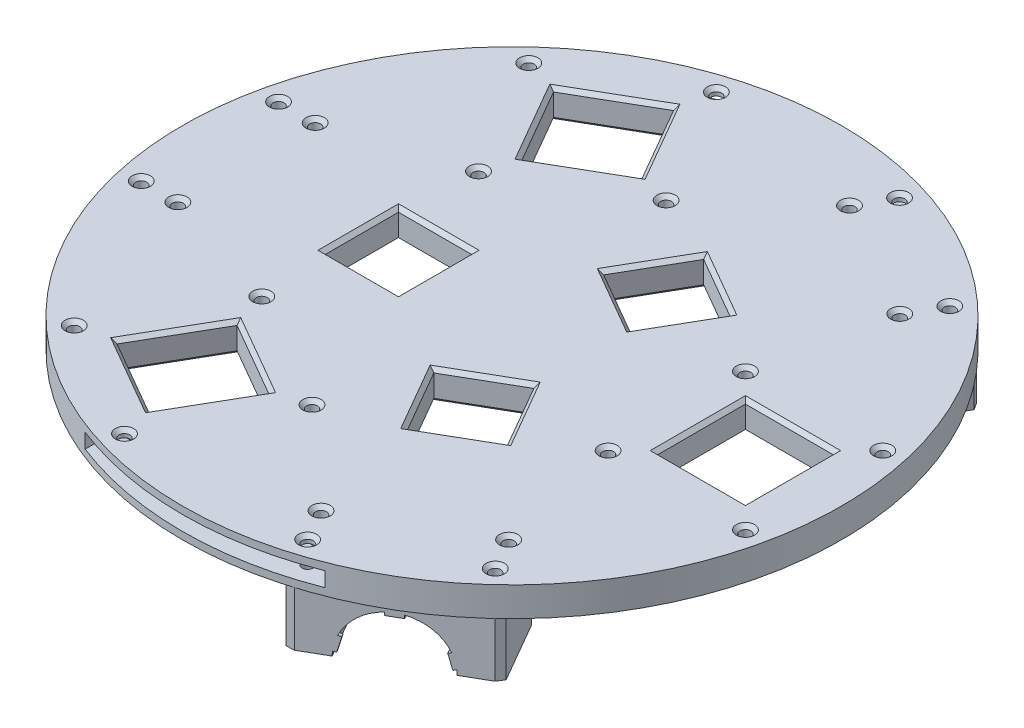
SolidWorks part; units mm, degrees
ref_plane "Plano frontal" through (0, 0, 0) normal (0, 0, 1) x (1, 0, 0)
ref_plane "Plano superior" through (0, 0, 0) normal (0, 1, 0) x (1, 0, 0)
ref_plane "Plano direito" through (0, 0, 0) normal (1, 0, 0) x (0, 0, -1)
sketch "Esboço2" plane through (0, 0, 0) normal (0, 1, 0) x (1, 0, 0)
  circle A0 centre (0, 0) radius 90
extrude "Ressalto-extrusão1" add sketch "Esboço2" along normal blind 8 contours A0
sketch "Esboço3" plane through (0, 0, 0) normal (0, -1, 0) x (-1, 0, 0)
  line L1 (67.5, 0) -> (67.5, -22)
  line L2 (67.5, 0) -> (67.5, 22)
  line L3 (67.5, -22) -> (86.5, -22)
  line L4 (87.5, -20) -> (87.5, 20)
  line L5 (86.5, 22) -> (67.5, 22)
  line L12 (87.5, -20) -> (86.5, -22)
  line L13 (87.5, 20) -> (86.5, 22)
  line L15 (-33.75, 58.4567) -> (-14.6974, 69.4567)
  line L16 (-33.75, 58.4567) -> (-52.8026, 47.4567)
  line L17 (-14.6974, 69.4567) -> (-24.1974, 85.9112)
  line L18 (-26.4295, 85.7772) -> (-61.0705, 65.7772)
  line L19 (-62.3026, 63.9112) -> (-52.8026, 47.4567)
  line L20 (-26.4295, 85.7772) -> (-24.1974, 85.9112)
  line L21 (-61.0705, 65.7772) -> (-62.3026, 63.9112)
  line L23 (-33.75, -58.4567) -> (-52.8026, -47.4567)
  line L24 (-33.75, -58.4567) -> (-14.6974, -69.4567)
  line L25 (-52.8026, -47.4567) -> (-62.3026, -63.9112)
  line L26 (-61.0705, -65.7772) -> (-26.4295, -85.7772)
  line L27 (-24.1974, -85.9112) -> (-14.6974, -69.4567)
  line L28 (-61.0705, -65.7772) -> (-62.3026, -63.9112)
  line L29 (-26.4295, -85.7772) -> (-24.1974, -85.9112)
extrude "Ressalto-extrusão2" add sketch "Esboço3" along normal blind 15
ref_plane "Plano2" through (0, 0, -90) normal (0, 0, -1) x (-1, 0, 0)
sketch "Esboço8" plane through (0, 0, -90) normal (0, 0, -1) x (-1, 0, 0)
  line L1 (0, 2) -> (32.75, 2)
  line L2 (32.75, 2) -> (32.75, 6)
  line L3 (32.75, 6) -> (-32.75, 6)
  line L4 (-32.75, 6) -> (-32.75, 2)
  line L5 (-32.75, 2) -> (0, 2)
extrude "Corte-extrusão1" cut sketch "Esboço8" against normal blind 14.5 contours L1 L2 L3 L4 L5
ref_plane "Plano3" through (0, 0, 90) normal (0, 0, 1) x (1, 0, 0)
sketch "Esboço9" plane through (0, 0, 90) normal (0, 0, 1) x (1, 0, 0)
  line L1 (0, 2) -> (32.75, 2)
  line L2 (32.75, 2) -> (32.75, 6)
  line L3 (32.75, 6) -> (-32.75, 6)
  line L4 (-32.75, 6) -> (-32.75, 2)
  line L5 (-32.75, 2) -> (0, 2)
extrude "Corte-extrusão2" cut sketch "Esboço9" against normal blind 14.5 contours L1 L2 L3 L4 L5
sketch "Esboço14" plane through (-67.5, 0, 0) normal (1, 0, 0) x (0, 0, -1)
  line L0 (22, -15) -> (-22, -15) construction
  line L3 (0, -3.5) -> (-2, -3.5)
  line L4 (0, -3.5) -> (2, -3.5)
  line L5 (2, -3.5) -> (2, -2.661)
  line L6 (-2, -3.5) -> (-2, -2.661)
  line L9 (-11.1081, -12.0236) -> (-11.6258, -13.9554)
  line L10 (-11.1081, -12.0236) -> (-10.5905, -10.0917)
  line L11 (-10.5905, -10.0917) -> (-11.4009, -9.8746)
  line L12 (-11.6258, -13.9554) -> (-12.4362, -13.7383)
  line L15 (11.1081, -12.0236) -> (10.5905, -10.0917)
  line L16 (11.1081, -12.0236) -> (11.6258, -13.9554)
  line L17 (11.6258, -13.9554) -> (12.4362, -13.7383)
  line L18 (10.5905, -10.0917) -> (11.4009, -9.8746)
  arc A0 (-12.4362, -13.7383) -> (12.4362, -13.7383) centre (0, -15) ccw
  arc A1 (-2, -2.661) -> (-11.4009, -9.8746) centre (0, -15) ccw
  arc A2 (11.4009, -9.8746) -> (2, -2.661) centre (0, -15) ccw
extrude "Corte-extrusão3" cut sketch "Esboço14" against normal through all
sketch "Esboço15" plane through (33.75, 0, 58.4567) normal (-0.5, 0, -0.866) x (-0.866, 0, 0.5)
  line L0 (22, -15) -> (-22, -15) construction
  line L3 (0, -3.5) -> (2, -3.5)
  line L4 (0, -3.5) -> (-2, -3.5)
  line L5 (-2, -3.5) -> (-2, -2.661)
  line L6 (2, -3.5) -> (2, -2.661)
  line L9 (-11.1081, -12.0236) -> (-10.5905, -10.0917)
  line L10 (-11.1081, -12.0236) -> (-11.6258, -13.9554)
  line L11 (-11.6258, -13.9554) -> (-12.4362, -13.7383)
  line L12 (-10.5905, -10.0917) -> (-11.4009, -9.8746)
  line L15 (11.1081, -12.0236) -> (11.6258, -13.9554)
  line L16 (11.1081, -12.0236) -> (10.5905, -10.0917)
  line L17 (10.5905, -10.0917) -> (11.4009, -9.8746)
  line L18 (11.6258, -13.9554) -> (12.4362, -13.7383)
  arc A0 (11.4009, -9.8746) -> (2, -2.661) centre (0, -15) ccw
  arc A1 (-2, -2.661) -> (-11.4009, -9.8746) centre (0, -15) ccw
  arc A2 (-12.4362, -13.7383) -> (12.4362, -13.7383) centre (0, -15) ccw
extrude "Corte-extrusão4" cut sketch "Esboço15" against normal through all
sketch "Esboço16" plane through (33.75, 0, -58.4567) normal (-0.5, 0, 0.866) x (0.866, 0, 0.5)
  line L0 (22, -15) -> (-22, -15) construction
  line L3 (0, -3.5) -> (2, -3.5)
  line L4 (0, -3.5) -> (-2, -3.5)
  line L5 (-2, -3.5) -> (-2, -2.661)
  line L6 (2, -3.5) -> (2, -2.661)
  line L9 (-11.1081, -12.0236) -> (-10.5905, -10.0917)
  line L10 (-11.1081, -12.0236) -> (-11.6258, -13.9554)
  line L11 (-11.6258, -13.9554) -> (-12.4362, -13.7383)
  line L12 (-10.5905, -10.0917) -> (-11.4009, -9.8746)
  line L15 (11.1081, -12.0236) -> (11.6258, -13.9554)
  line L16 (11.1081, -12.0236) -> (10.5905, -10.0917)
  line L17 (10.5905, -10.0917) -> (11.4009, -9.8746)
  line L18 (11.6258, -13.9554) -> (12.4362, -13.7383)
  arc A0 (11.4009, -9.8746) -> (2, -2.661) centre (0, -15) ccw
  arc A1 (-2, -2.661) -> (-11.4009, -9.8746) centre (0, -15) ccw
  arc A2 (-12.4362, -13.7383) -> (12.4362, -13.7383) centre (0, -15) ccw
extrude "Corte-extrusão5" cut sketch "Esboço16" against normal through all
sketch "Esboço17" plane through (33.75, 0, 58.4567) normal (-0.5, 0, -0.866) x (-0.866, 0, 0.5)
  circle A0 centre (0, -15) radius 12.5
extrude "Corte-extrusão6" cut sketch "Esboço17" against normal blind 19
sketch "Esboço18" plane through (-67.5, 0, 0) normal (1, 0, 0) x (0, 0, -1)
  circle A0 centre (0, -15) radius 12.5
extrude "Corte-extrusão7" cut sketch "Esboço18" against normal blind 19 contours A0
sketch "Esboço19" plane through (33.75, 0, -58.4567) normal (-0.5, 0, 0.866) x (0.866, 0, 0.5)
  circle A0 centre (0, -15) radius 12.5
extrude "Corte-extrusão8" cut sketch "Esboço19" against normal blind 19
sketch "Esboço20" plane through (0, -15, 0) normal (0, -1, 0) x (1, 0, 0)
  circle A0 centre (-82.5, 18.75) radius 1.5
  circle A1 centre (-72.5, 18.75) radius 1.5
  circle A2 centre (-82.5, -18.75) radius 1.5
  circle A3 centre (-72.5, -18.75) radius 1.5
  circle A4 centre (25.012, -80.8221) radius 1.5
  circle A5 centre (20.012, -72.1618) radius 1.5
  circle A6 centre (57.488, -62.0721) radius 1.5
  circle A7 centre (52.488, -53.4118) radius 1.5
  circle A8 centre (57.488, 62.0721) radius 1.5
  circle A9 centre (52.488, 53.4118) radius 1.5
  circle A10 centre (25.012, 80.8221) radius 1.5
  circle A11 centre (20.012, 72.1618) radius 1.5
extrude "Corte-extrusão9" cut sketch "Esboço20" against normal through all
sketch "Esboço21" plane through (0, 0, 0) normal (0, -1, 0) x (-1, 0, 0)
  line L0 (-10.5, 18.1865) -> (-1.8397, 23.1865)
  line L1 (21, 0) -> (21, -10)
  line L2 (21, -10) -> (41, -10)
  line L3 (41, -10) -> (41, 10)
  line L4 (41, 10) -> (21, 10)
  line L5 (21, 10) -> (21, 0)
  line L6 (-1.8397, 23.1865) -> (-11.8397, 40.507)
  line L7 (-51.75, 0) -> (-51.75, -12)
  line L8 (-51.75, -12) -> (-75.75, -12)
  line L9 (-75.75, -12) -> (-75.75, 12)
  line L10 (-75.75, 12) -> (-51.75, 12)
  line L11 (-51.75, 12) -> (-51.75, 0)
  line L13 (-11.8397, 40.507) -> (-29.1603, 30.507)
  line L14 (-29.1603, 30.507) -> (-19.1603, 13.1865)
  line L15 (-19.1603, 13.1865) -> (-10.5, 18.1865)
  line L16 (25.875, -44.8168) -> (36.2673, -38.8168)
  line L17 (36.2673, -38.8168) -> (48.2673, -59.6014)
  line L18 (48.2673, -59.6014) -> (27.4827, -71.6014)
  line L19 (27.4827, -71.6014) -> (15.4827, -50.8168)
  line L20 (15.4827, -50.8168) -> (25.875, -44.8168)
  line L22 (-10.5, -18.1865) -> (-19.1603, -13.1865)
  line L23 (-19.1603, -13.1865) -> (-29.1603, -30.507)
  line L24 (-29.1603, -30.507) -> (-11.8397, -40.507)
  line L25 (-11.8397, -40.507) -> (-1.8397, -23.1865)
  line L26 (-1.8397, -23.1865) -> (-10.5, -18.1865)
  line L27 (25.875, 44.8168) -> (15.4827, 50.8168)
  line L28 (15.4827, 50.8168) -> (27.4827, 71.6014)
  line L29 (27.4827, 71.6014) -> (48.2673, 59.6014)
  line L30 (48.2673, 59.6014) -> (36.2673, 38.8168)
  line L31 (36.2673, 38.8168) -> (25.875, 44.8168)
  circle A0 centre (-45, -18.75) radius 1.5
  circle A1 centre (-82.5, -18.75) radius 1.5
  circle A2 centre (-82.5, 18.75) radius 1.5
  circle A3 centre (-45, 18.75) radius 1.5
  circle A4 centre (38.738, -29.5961) radius 1.5
  circle A5 centre (57.488, -62.0721) radius 1.5
  circle A6 centre (25.012, -80.8221) radius 1.5
  circle A7 centre (6.262, -48.3461) radius 1.5
  circle A8 centre (6.262, 48.3461) radius 1.5
  circle A9 centre (25.012, 80.8221) radius 1.5
  circle A10 centre (57.488, 62.0721) radius 1.5
  circle A11 centre (38.738, 29.5961) radius 1.5
extrude "Corte-extrusão10" cut sketch "Esboço21" against normal through all
chamfer "Chanfro5" distance 1 angle 45 24 edges at (20.012, 8, -73.6618) (25.012, 8, -82.3221) (57.488, 8, -63.5721) (52.488, 8, -54.9118) (82.5, 8, -20.25) (82.5, 8, 17.25) (45, 8, -20.25) (45, 8, 17.25) (-25.012, 8, -82.3221) (-6.262, 8, -49.8461) (57.488, 8, 60.5721) (52.488, 8, 51.9118) (25.012, 8, 79.3221) (20.012, 8, 70.6618) (-38.738, 8, -31.0961) (-57.488, 8, -63.5721) (-72.5, 8, -20.25) (-82.5, 8, -20.25) (-82.5, 8, 17.25) (-72.5, 8, 17.25) (-6.262, 8, 46.8461) (-38.738, 8, 28.0961) (-25.012, 8, 79.3221) (-57.488, 8, 60.5721)
chamfer "Chanfro6" distance 1 angle 45 24 edges at (-37.875, 8, -65.6014) (-21.4827, 8, -61.2091) (-25.875, 8, -44.8168) (-42.2673, 8, -49.2091) (-41, 8, 0) (-31, 8, 10) (-21, 8, 0) (-31, 8, -10) (6.8397, 8, -31.8468) (10.5, 8, -18.1865) (24.1603, 8, -21.8468) (20.5, 8, -35.507) (63.75, 8, -12) (75.75, 8, 0) (51.75, 8, 0) (63.75, 8, 12) (24.1603, 8, 21.8468) (20.5, 8, 35.507) (6.8397, 8, 31.8468) (10.5, 8, 18.1865) (-42.2673, 8, 49.2091) (-25.875, 8, 44.8168) (-21.4827, 8, 61.2091) (-37.875, 8, 65.6014)
chamfer "Chanfro7" distance 1 angle 45 4 edges at (-82.5, -15, -20.25) (-72.5, -15, -20.25) (-82.5, -15, 17.25) (-72.5, -15, 17.25)
chamfer "Chanfro8" distance 1 angle 45 12 edges at (-25.012, 0, -82.3221) (-57.488, 0, -63.5721) (-38.738, 0, -31.0961) (-6.262, 0, -49.8461) (82.5, 0, 17.25) (82.5, 0, -20.25) (45, 0, -20.25) (45, 0, 17.25) (-25.012, 0, 79.3221) (-6.262, 0, 46.8461) (-38.738, 0, 28.0961) (-57.488, 0, 60.5721)
chamfer "Chanfro9" distance 1 angle 45 8 edges at (20.012, -15, -73.6618) (25.012, -15, -82.3221) (57.488, -15, -63.5721) (52.488, -15, -54.9118) (52.488, -15, 51.9118) (57.488, -15, 60.5721) (20.012, -15, 70.6618) (25.012, -15, 79.3221)
chamfer "Chanfro10" distance 1 angle 45 24 edges at (-37.875, 0, 65.6014) (-21.4827, 0, 61.2091) (-25.875, 0, 44.8168) (-42.2673, 0, 49.2091) (-21, 0, 0) (-31, 0, -10) (-41, 0, 0) (-31, 0, 10) (6.8397, 0, 31.8468) (20.5, 0, 35.507) (10.5, 0, 18.1865) (24.1603, 0, 21.8468) (-21.4827, 0, -61.2091) (-37.875, 0, -65.6014) (-42.2673, 0, -49.2091) (-25.875, 0, -44.8168) (6.8397, 0, -31.8468) (10.5, 0, -18.1865) (24.1603, 0, -21.8468) (20.5, 0, -35.507) (75.75, 0, 0) (63.75, 0, -12) (51.75, 0, 0) (63.75, 0, 12)
